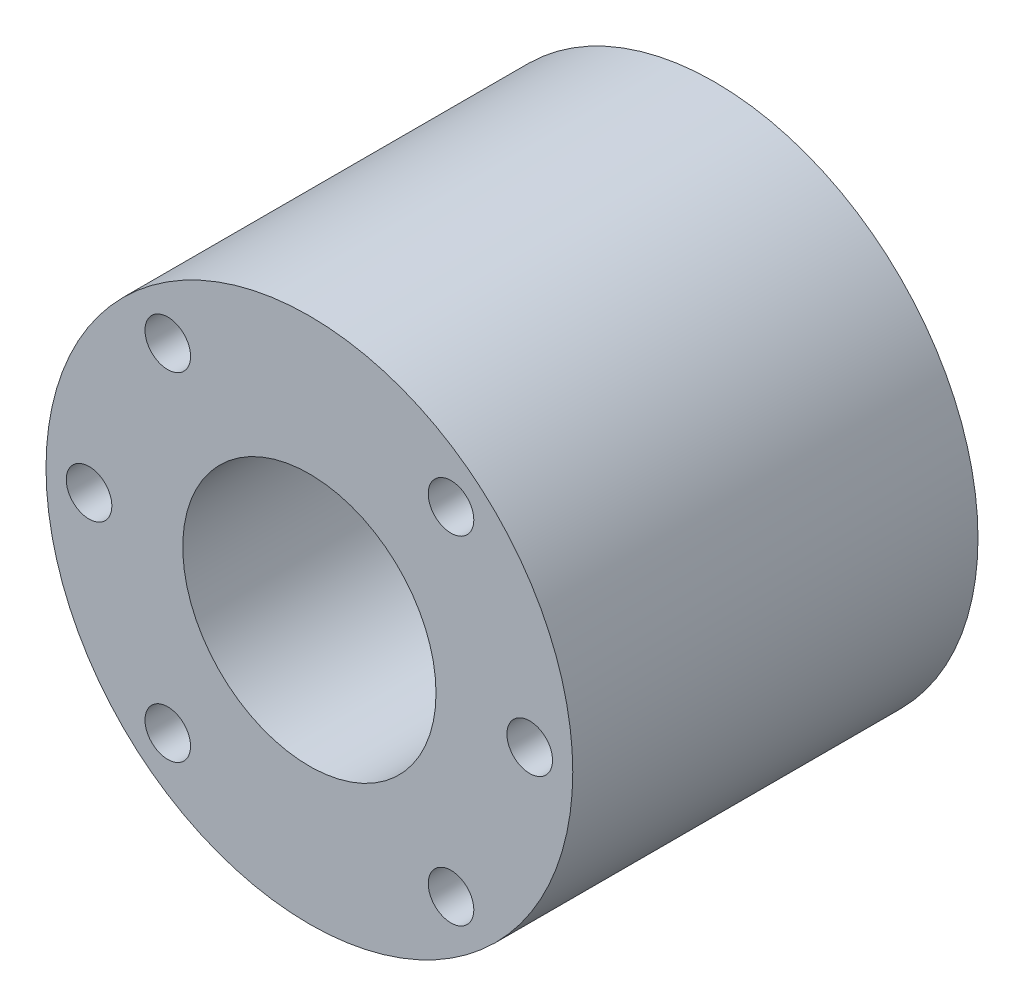
SolidWorks part; units mm, degrees
material "ABS"
ref_plane "前视基准面" through (0, 0, 0) normal (0, 0, 1) x (1, 0, 0)
ref_plane "上视基准面" through (0, 0, 0) normal (0, 1, 0) x (1, 0, 0)
ref_plane "右视基准面" through (0, 0, 0) normal (1, 0, 0) x (0, 0, -1)
sketch "草图1" plane through (0, 0, 0) normal (0, 0, 1) x (1, 0, 0)
  line L0 (-21.75, 0) -> (21.75, 0) construction
  line L1 (0, 0) -> (-13.9806, -16.6615) construction
  line L2 (0, 0) -> (13.9806, 16.6615) construction
  line L3 (-13.9806, 16.6615) -> (0, 0) construction
  line L4 (0, 0) -> (13.9806, -16.6615) construction
  circle A0 centre (0, 0) radius 21.75 construction
  circle A1 centre (0, 0) radius 26
  circle A2 centre (-21.75, 0) radius 2.25
  circle A3 centre (-13.9806, 16.6615) radius 2.25
  circle A4 centre (-13.9806, -16.6615) radius 2.25
  circle A5 centre (13.9806, -16.6615) radius 2.25
  circle A6 centre (21.75, 0) radius 2.25
  circle A7 centre (13.9806, 16.6615) radius 2.25
  dimension "D1" = 52
  dimension "D2" = 43.5
  dimension "D7" = 4.5
  dimension "D3" = 50
extrude "凸台-拉伸1" add sketch "草图1" along normal blind 40
sketch "草图2" plane through (0, 0, 40) normal (0, 0, 1) x (1, 0, 0)
  circle A0 centre (0, 0) radius 12.5
  dimension "D1" = 25
extrude "切除-拉伸1" cut sketch "草图2" against normal through all
